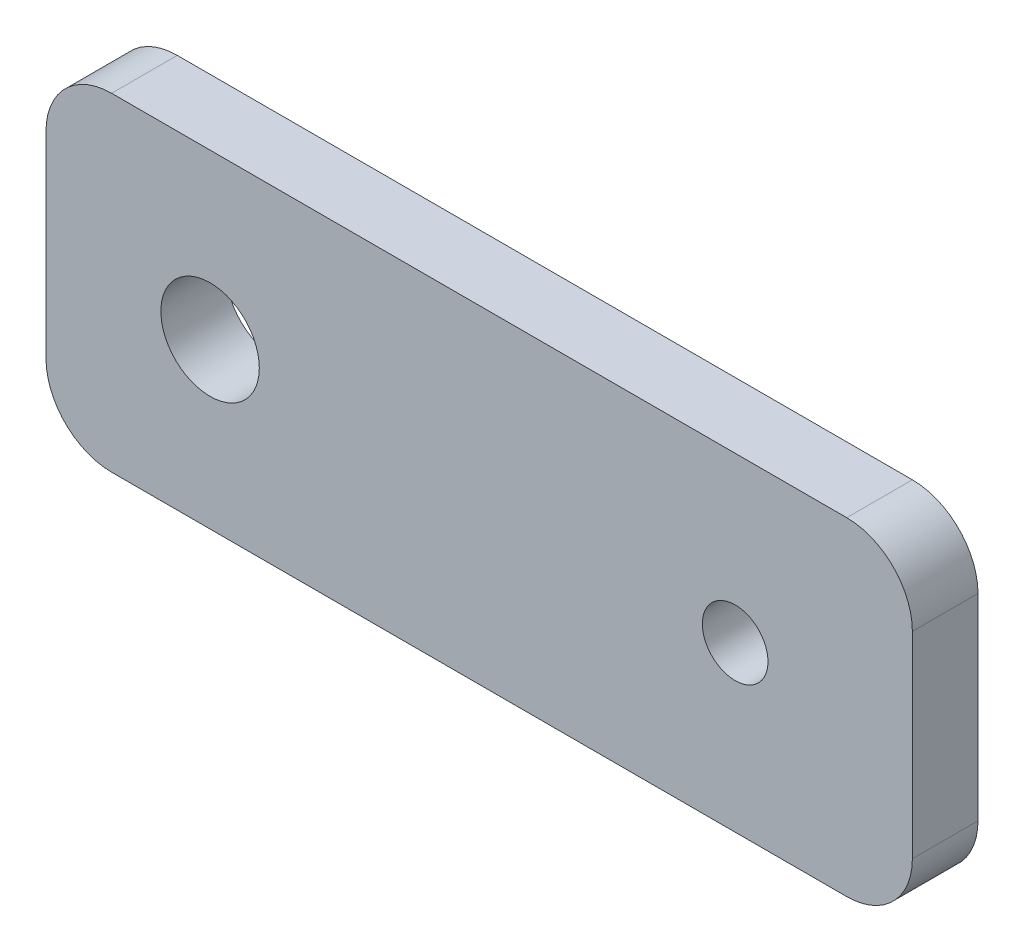
SolidWorks part; units mm, degrees
ref_plane "Front Plane" through (0, 0, 0) normal (0, 0, 1) x (1, 0, 0)
ref_plane "Top Plane" through (0, 0, 0) normal (0, 1, 0) x (1, 0, 0)
ref_plane "Right Plane" through (0, 0, 0) normal (1, 0, 0) x (0, 0, -1)
sketch "Sketch1" plane through (0, 0, 0) normal (0, 0, 1) x (1, 0, 0)
  line L1 (0, 0) -> (-33.528, 0)
  line L2 (0, 0) -> (0, 12.7)
  line L3 (0, 12.7) -> (-33.528, 12.7)
  line L4 (-33.528, 0) -> (-33.528, 12.7)
  dimension "D1" = 33.528
  dimension "D2" = 12.7
extrude "Boss-Extrude1" add sketch "Sketch1" along normal blind 2.54
fillet "Fillet1" radius 2.54 4 edges at (-33.528, 0, 1.27) (0, 0, 1.27) (0, 12.7, 1.27) (-33.528, 12.7, 1.27)
sketch "Sketch2" plane through (0, 0, 2.54) normal (0, 0, 1) x (1, 0, 0)
  line L0 (-33.528, 10.16) -> (-33.528, 2.54) construction
  line L1 (-33.528, 10.16) -> (-33.528, 2.54) construction
  circle A0 centre (-27.178, 6.35) radius 1.905
  circle A1 centre (-6.858, 6.35) radius 1.27
  point P4 (-33.528, 6.35)
  dimension "D1" = 2.54
  dimension "D2" = 20.32
  dimension "D3" = 6.35
  dimension "D4" = 3.81
extrude "Cut-Extrude1" cut sketch "Sketch2" against normal through all
